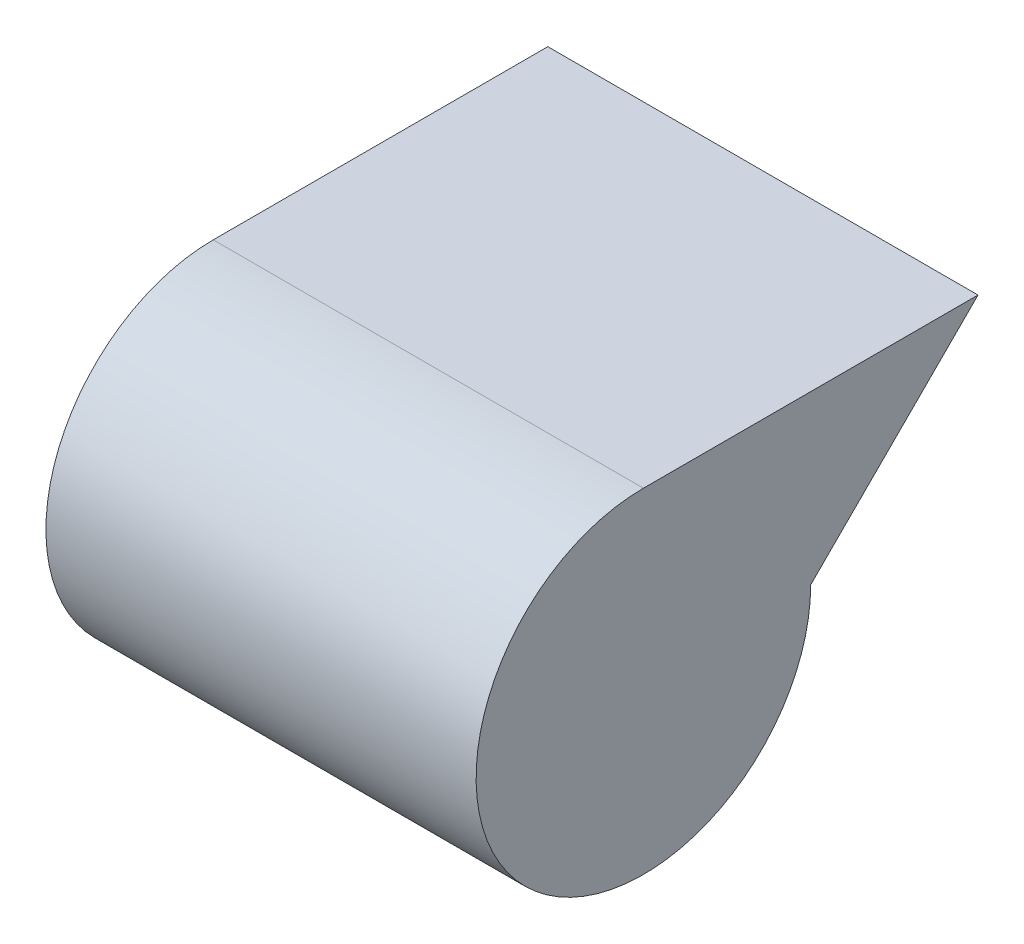
SolidWorks part; units mm, degrees
ref_plane "前视基准面" through (0, 0, 0) normal (0, 0, 1) x (1, 0, 0)
ref_plane "上视基准面" through (0, 0, 0) normal (0, 1, 0) x (1, 0, 0)
ref_plane "右视基准面" through (0, 0, 0) normal (1, 0, 0) x (0, 0, -1)
other "Configuration Table"
sketch "草图1" plane through (0, 0, 0) normal (1, 0, 0) x (0, 0, -1)
  circle A0 centre (0, 0) radius 35
  dimension "D1" = 70
extrude "凸台-拉伸1" add sketch "草图1" along normal blind 90
sketch "草图3" plane through (0, 0, 0) normal (1, 0, 0) x (0, 0, -1)
  line L0 (0, 35) -> (65.1944, 35)
  line L1 (0, -35) -> (70, 35)
  line L2 (70, 35) -> (65.1944, 35)
  line L3 (0, 35) -> (0, -35)
  circle A0 centre (0, 0) radius 35 construction
extrude "凸台-拉伸2" add sketch "草图3" along normal blind 90
sketch "草图4" plane through (90, 0, 0) normal (1, 0, 0) x (0, 0, -1)
  circle A0 centre (0, 0) radius 35
